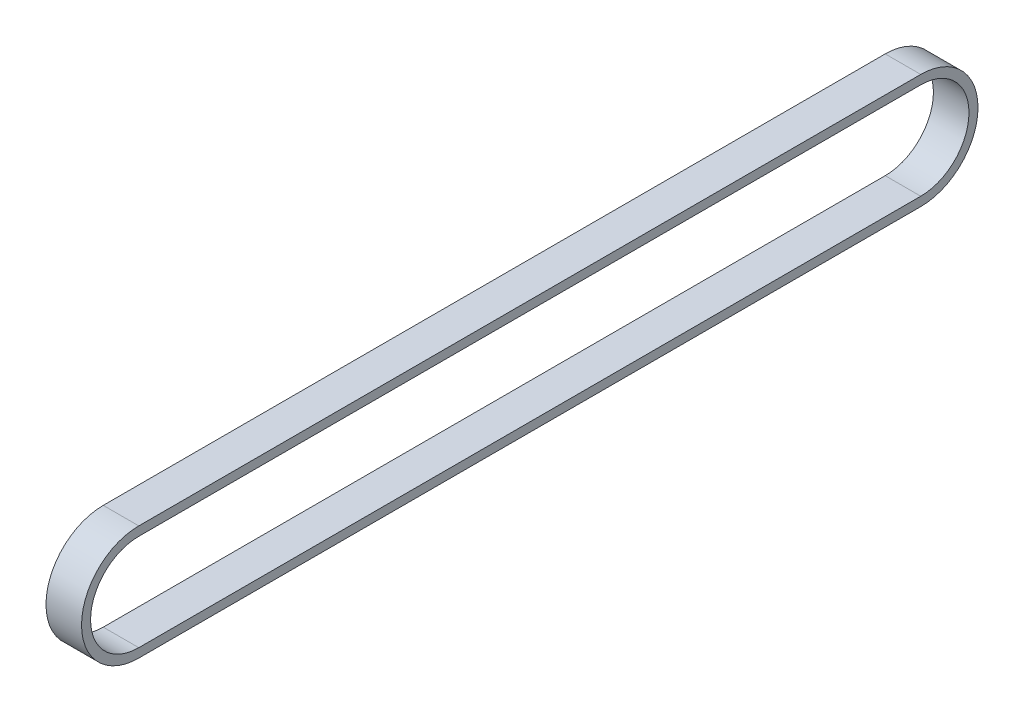
SolidWorks part; units mm, degrees
material "6061-T6 (SS)"
ref_plane "Front Plane" through (0, 0, 0) normal (0, 0, 1) x (1, 0, 0)
ref_plane "Top Plane" through (0, 0, 0) normal (0, 1, 0) x (1, 0, 0)
ref_plane "Right Plane" through (0, 0, 0) normal (1, 0, 0) x (0, 0, -1)
sketch "Sketch1" plane through (0, 0, 0) normal (1, 0, 0) x (0, 0, -1)
  line L0 (330, 22.2817) -> (0, 22.2817) construction
  line L1 (0, -22.2817) -> (330, -22.2817) construction
  line L2 (330, 24.1613) -> (0, 24.1613)
  line L3 (0, -24.1613) -> (330, -24.1613)
  line L4 (330, 20.3513) -> (0, 20.3513)
  line L5 (0, -20.3513) -> (330, -20.3513)
  circle A0 centre (0, 0) radius 22.2817 construction
  circle A1 centre (330, 0) radius 22.2817 construction
  arc A2 (0, 22.2817) -> (0, -22.2817) centre (0, 0) ccw construction
  arc A3 (330, -22.2817) -> (330, 22.2817) centre (330, 0) ccw construction
  arc A4 (0, 24.1613) -> (0, -24.1613) centre (0, 0) ccw
  arc A5 (330, -24.1613) -> (330, 24.1613) centre (330, 0) ccw
  arc A6 (0, 20.3513) -> (0, -20.3513) centre (0, 0) ccw
  arc A7 (330, -20.3513) -> (330, 20.3513) centre (330, 0) ccw
  dimension "D1" = 44.5634
  dimension "D3" = 1.9304
  dimension "D2" = 3.81
extrude "Boss-Extrude1" add sketch "Sketch1" along normal blind 15
equation "\"D1@Sketch1\"=28*5mm/pi"
equation "\"D4@Sketch1\"=160*5mm"
